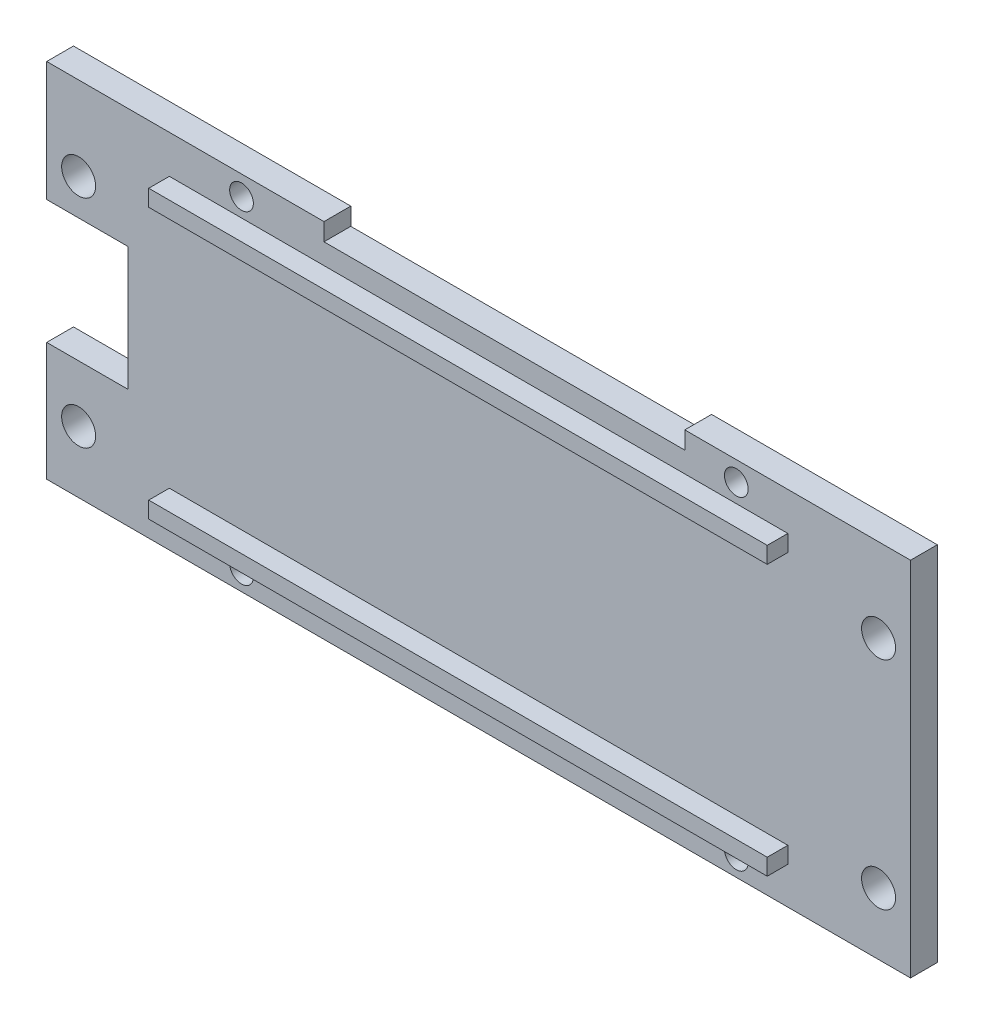
SolidWorks part; units mm, degrees
ref_plane "前视基准面" through (0, 0, 0) normal (0, 0, 1) x (1, 0, 0)
ref_plane "上视基准面" through (0, 0, 0) normal (0, 1, 0) x (1, 0, 0)
ref_plane "右视基准面" through (0, 0, 0) normal (1, 0, 0) x (0, 0, -1)
other "Configuration Table"
sketch "2.6 mm removable shelf - wiring notch and clamp holes profile" plane through (0, 0, 0) normal (0, 0, 1) x (1, 0, 0)
  line L0 (-41.9, -24.5) -> (41.9, -24.5)
  line L1 (41.9, -24.5) -> (41.9, 10.6)
  line L2 (41.9, 10.6) -> (20, 10.6)
  line L3 (20, 10.6) -> (20, 8.9)
  line L4 (20, 8.9) -> (-15, 8.9)
  line L5 (-15, 8.9) -> (-15, 10.6)
  line L6 (-15, 10.6) -> (-41.9, 10.6)
  line L7 (-41.9, 10.6) -> (-41.9, -1)
  line L8 (-41.9, -1) -> (-34, -1)
  line L9 (-34, -1) -> (-34, -13)
  line L10 (-34, -13) -> (-41.9, -13)
  line L11 (-41.9, -13) -> (-41.9, -24.5)
  circle A0 centre (-38.8, -18.5) radius 1.65
  circle A1 centre (38.8, -18.5) radius 1.65
  circle A2 centre (-38.8, 2.5) radius 1.65
  circle A3 centre (38.8, 2.5) radius 1.65
  circle A4 centre (-23, -22.7) radius 1.15
  circle A5 centre (25, -22.7) radius 1.15
  circle A6 centre (-23, 8.7) radius 1.15
  circle A7 centre (25, 8.7) radius 1.15
extrude "2.6 mm removable shelf - wiring notch and clamp holes" add sketch "2.6 mm removable shelf - wiring notch and clamp holes profile" along normal blind 2.6
sketch "Controller board edge rests profile" plane through (0, 0, 0) normal (0, 0, 1) x (1, 0, 0)
  line L0 (-30, -20.9) -> (30, -20.9)
  line L1 (30, -20.9) -> (30, -19.3)
  line L2 (30, -19.3) -> (-30, -19.3)
  line L3 (-30, -19.3) -> (-30, -20.9)
  line L4 (-30, 5.3) -> (30, 5.3)
  line L5 (30, 5.3) -> (30, 6.9)
  line L6 (30, 6.9) -> (-30, 6.9)
  line L7 (-30, 6.9) -> (-30, 5.3)
extrude "Controller board edge rests" add sketch "Controller board edge rests profile" along normal blind 2 from offset 2.6
